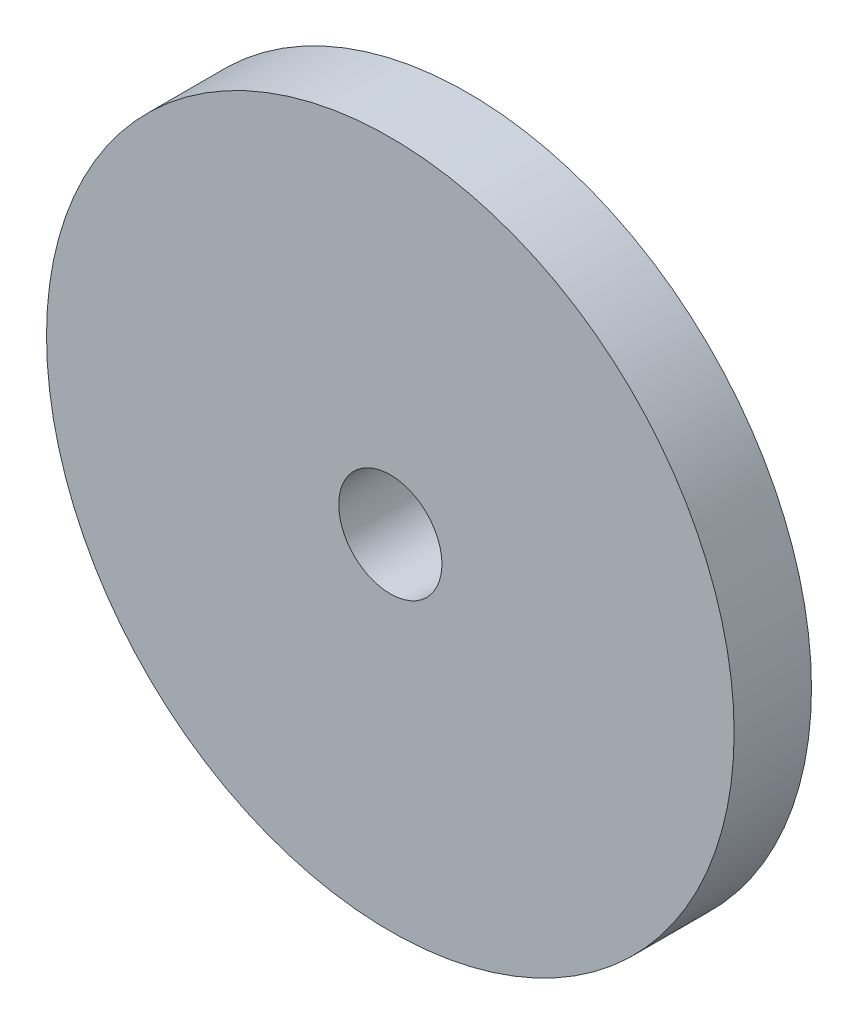
SolidWorks part; units mm, degrees
ref_plane "Front Plane" through (0, 0, 0) normal (0, 0, 1) x (1, 0, 0)
ref_plane "Top Plane" through (0, 0, 0) normal (0, 1, 0) x (1, 0, 0)
ref_plane "Right Plane" through (0, 0, 0) normal (1, 0, 0) x (0, 0, -1)
sketch "Sketch1" plane through (0, 0, 0) normal (0, 0, 1) x (1, 0, 0)
  circle A0 centre (0, 0) radius 100
  circle A1 centre (0, 0) radius 15
  dimension "D1" = 200
  dimension "D2" = 30
extrude "Boss-Extrude1" add sketch "Sketch1" along normal blind 22.5
